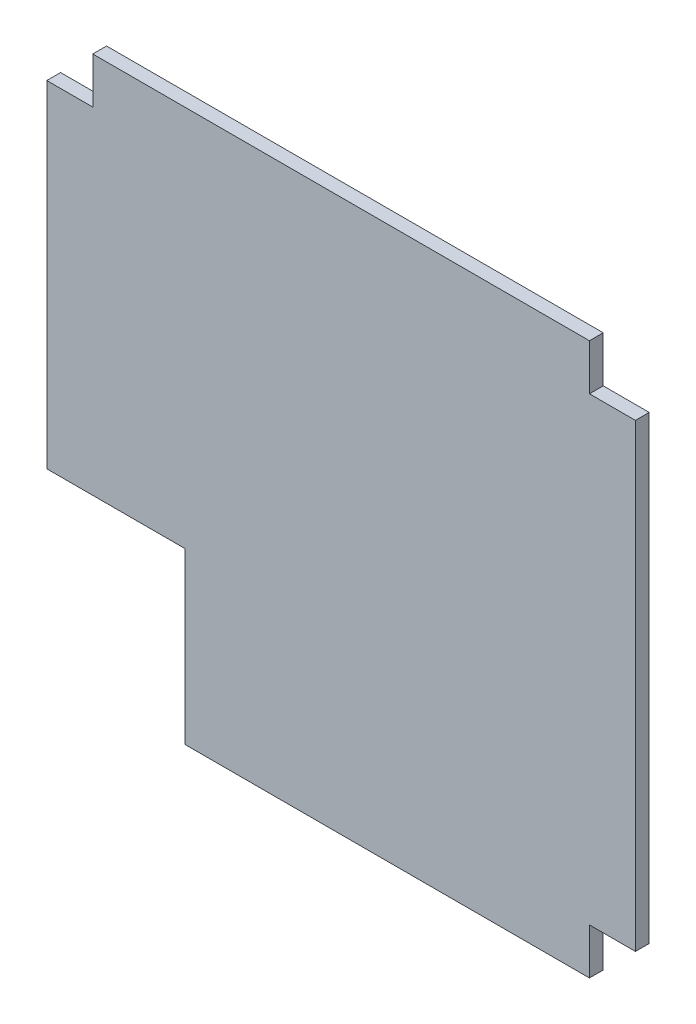
SolidWorks part; units mm, degrees
ref_plane "Alzado" through (0, 0, 0) normal (0, 0, 1) x (1, 0, 0)
ref_plane "Planta" through (0, 0, 0) normal (0, 1, 0) x (1, 0, 0)
ref_plane "Vista lateral" through (0, 0, 0) normal (1, 0, 0) x (0, 0, -1)
sketch "Croquis1" plane through (0, 0, 0) normal (0, 0, 1) x (1, 0, 0)
  line L0 (-132.5957, 140) -> (-132.5957, -260)
  line L1 (-132.5957, -260) -> (294.0443, -260)
  line L2 (294.0443, -260) -> (294.0443, 140)
  line L3 (294.0443, 140) -> (-132.5957, 140)
  dimension "D1" = 400
  dimension "D2" = 426.64
extrude "Saliente-Extruir1" add sketch "Croquis1" along normal blind 10
sketch "Croquis2" plane through (0, 0, 10) normal (0, 0, 1) x (1, 0, 0)
  line L2 (-132.5957, -260) -> (-99.2757, -260)
  line L3 (-132.5957, 140) -> (-99.2757, 140)
  line L4 (-132.5957, 140) -> (-132.5957, 106.68)
  line L5 (-132.5957, 106.68) -> (-99.2757, 106.68)
  line L6 (-99.2757, 140) -> (-99.2757, 106.68)
  line L7 (294.0443, 140) -> (260.7243, 140)
  line L8 (294.0443, 140) -> (294.0443, 106.68)
  line L9 (294.0443, 106.68) -> (260.7243, 106.68)
  line L10 (260.7243, 140) -> (260.7243, 106.68)
  line L11 (294.0443, -260) -> (260.7243, -260)
  line L12 (294.0443, -260) -> (294.0443, -226.68)
  line L13 (294.0443, -226.68) -> (260.7243, -226.68)
  line L14 (260.7243, -260) -> (260.7243, -226.68)
  line L15 (-132.5957, -260) -> (-132.5957, -226.68)
  line L16 (-132.5957, -226.68) -> (-99.2757, -226.68)
  line L17 (-99.2757, -260) -> (-99.2757, -226.68)
  dimension "D1" = 33.32
  dimension "D2" = 33.32
  dimension "D3" = 33.32
  dimension "D4" = 33.32
  dimension "D5" = 33.32
  dimension "D6" = 33.32
  dimension "D7" = 33.32
  dimension "D8" = 33.32
extrude "Cortar-Extruir1" cut sketch "Croquis2" against normal through all
sketch "Croquis3" plane through (0, 0, 10) normal (0, 0, 1) x (1, 0, 0)
  line L0 (-132.5957, -137.05) -> (-132.5957, -226.68)
  line L2 (-132.5957, -226.68) -> (-99.2757, -226.68)
  line L3 (-132.5957, 106.68) -> (-132.5957, -226.68) construction
  line L4 (-99.2757, -226.68) -> (-99.2757, -260)
  line L5 (-132.5957, -137.05) -> (-32.5957, -137.05)
  line L6 (-32.5957, -137.05) -> (-32.5957, -260)
  line L7 (-99.2757, -260) -> (-32.5957, -260)
extrude "Cortar-Extruir2" cut sketch "Croquis3" against normal through all
